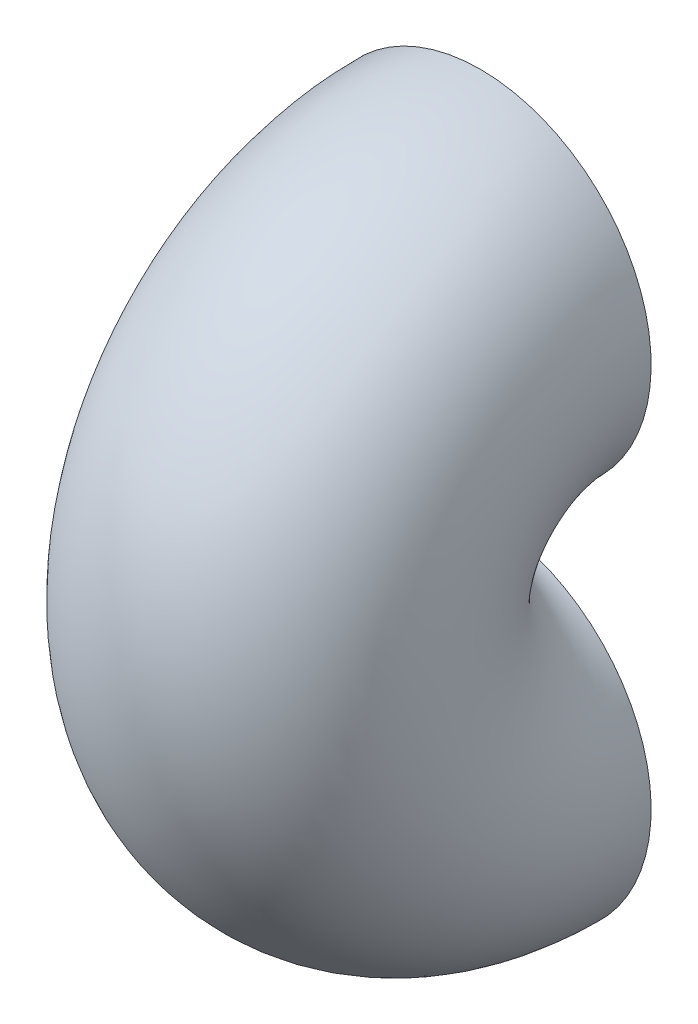
SolidWorks part; units mm, degrees
ref_plane "Plan de face" through (0, 0, 0) normal (0, 0, 1) x (1, 0, 0)
ref_plane "Plan de dessus" through (0, 0, 0) normal (0, 1, 0) x (1, 0, 0)
ref_plane "Plan de droite" through (0, 0, 0) normal (1, 0, 0) x (0, 0, -1)
sketch "Esquisse1" plane through (0, 0, 0) normal (0, 0, 1) x (1, 0, 0)
  line L0 (-314.9031, -40) -> (354.4112, -40) construction
  circle A0 centre (0, 0) radius 32.5
  circle A1 centre (0, 0) radius 35.5
  dimension "D1" = 65
  dimension "D2" = 71
  dimension "D3" = 40
revolve "Révolution1" add sketch "Esquisse1" angle 180 about L0
